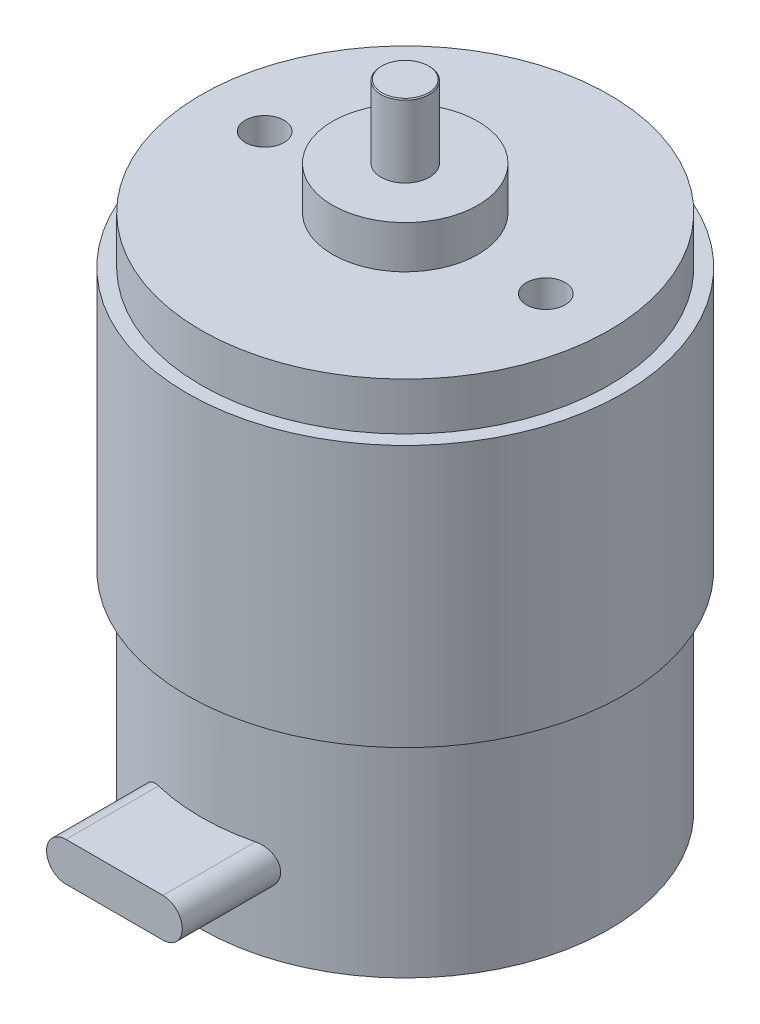
SolidWorks part; units mm, degrees
ref_plane "正面" through (0, 0, 0) normal (0, 0, 1) x (1, 0, 0)
ref_plane "平面" through (0, 0, 0) normal (0, 1, 0) x (1, 0, 0)
ref_plane "右側面" through (0, 0, 0) normal (1, 0, 0) x (0, 0, -1)
sketch "ｽｹｯﾁ1" plane through (0, 0, 0) normal (0, 1, 0) x (1, 0, 0)
  circle A0 centre (0, 0) radius 7.5
  dimension "D1" = 15
extrude "ﾎﾞｽ - 押し出し1" add sketch "ｽｹｯﾁ1" along normal blind 4.3
sketch "ｽｹｯﾁ2" plane through (0, 4.3, 0) normal (0, 1, 0) x (1, 0, 0)
  circle A0 centre (0, 0) radius 21.05
  dimension "D1" = 42.1
extrude "ﾎﾞｽ - 押し出し2" add sketch "ｽｹｯﾁ2" along normal blind 53.5
sketch "ｽｹｯﾁ3" plane through (0, 57.8, 0) normal (0, 1, 0) x (1, 0, 0)
  circle A0 centre (0, 0) radius 7.5
  dimension "D1" = 15
extrude "ﾎﾞｽ - 押し出し3" add sketch "ｽｹｯﾁ3" along normal blind 4.4
ref_plane "平面1" through (0, 52.9, 0) normal (0, 1, 0) x (1, 0, 0)
sketch "ｽｹｯﾁ5" plane through (0, 52.9, 0) normal (0, 1, 0) x (1, 0, 0)
  circle A0 centre (0, 0) radius 22.5
  dimension "D1" = 45
extrude "ﾎﾞｽ - 押し出し5" add sketch "ｽｹｯﾁ5" against normal blind 27
ref_plane "平面2" through (0, 69.7, 0) normal (0, 1, 0) x (1, 0, 0)
sketch "ｽｹｯﾁ6" plane through (0, 69.7, 0) normal (0, 1, 0) x (1, 0, 0)
  circle A0 centre (0, 0) radius 2.5
  dimension "D1" = 5
extrude "ﾎﾞｽ - 押し出し6" add sketch "ｽｹｯﾁ6" against normal blind 70
sketch "ｽｹｯﾁ7" plane through (0, 57.8, 0) normal (0, 1, 0) x (1, 0, 0)
  line L0 (-21.05, 0) -> (21.05, 0) construction
  circle A0 centre (0, 0) radius 21.05 construction
  circle A1 centre (14.5, 0) radius 2
  circle A2 centre (-14.5, 0) radius 2
  point P11 (0, 0)
  dimension "D1" = 4
  dimension "D3" = 14.5
  dimension "D2" = 2
extrude "ｶｯﾄ - 押し出し1" cut sketch "ｽｹｯﾁ7" against normal blind 5
chamfer "面取り1" distance 0.1 angle 45 2 edges at (0, -0.3, 2.5) (0, 69.7, 2.5)
sketch "ｽｹｯﾁ8" plane through (0, 0, 0) normal (0, 0, 1) x (1, 0, 0)
  line L0 (0, -3.7405) -> (0, 82.5344) construction
  line L1 (-5, 12.3) -> (5, 12.3) construction
  line L2 (-5, 14.3) -> (5, 14.3)
  line L3 (-5, 10.3) -> (5, 10.3)
  line L4 (-21.05, 4.3) -> (21.05, 4.3) construction
  arc A0 (-5, 14.3) -> (-5, 10.3) centre (-5, 12.3) ccw
  arc A1 (5, 10.3) -> (5, 14.3) centre (5, 12.3) ccw
  point P5 (0, 12.3)
  dimension "D3" = 2
  dimension "D1" = 10
  dimension "D2" = 10
extrude "ﾎﾞｽ - 押し出し7" add sketch "ｽｹｯﾁ8" along normal blind 30
